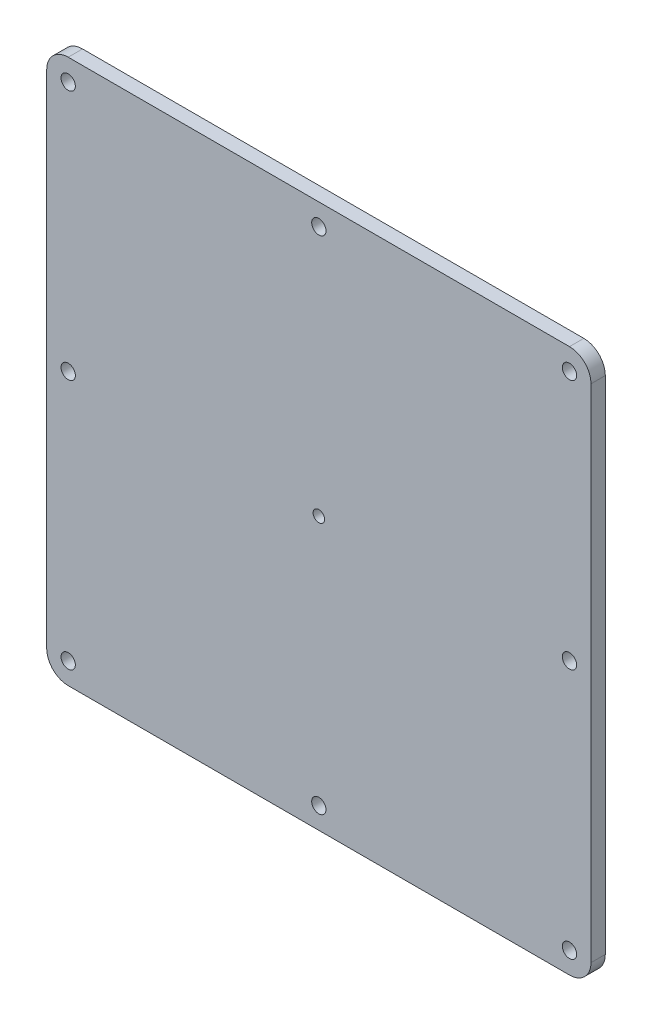
SolidWorks part; units mm, degrees
ref_plane "Front Plane" through (0, 0, 0) normal (0, 0, 1) x (1, 0, 0)
ref_plane "Top Plane" through (0, 0, 0) normal (0, 1, 0) x (1, 0, 0)
ref_plane "Right Plane" through (0, 0, 0) normal (1, 0, 0) x (0, 0, -1)
sketch "Sketch2" plane through (0, 0, 0) normal (0, 0, 1) x (1, 0, 0)
  line L0 (-175, 175) -> (175, 175) construction
  line L1 (-175, 190) -> (175, 190)
  line L2 (-190, 175) -> (-190, -175)
  line L3 (-175, -190) -> (175, -190)
  line L4 (190, 175) -> (190, -175)
  line L5 (-190, 190) -> (190, -190) construction
  line L6 (-190, -190) -> (190, 190) construction
  line L7 (175, 175) -> (175, -175) construction
  line L8 (175, -175) -> (-175, -175) construction
  line L9 (-175, -175) -> (-175, 175) construction
  arc A0 (-190, -175) -> (-175, -190) centre (-175, -175) ccw
  arc A1 (175, -190) -> (190, -175) centre (175, -175) ccw
  arc A2 (175, 190) -> (190, 175) centre (175, 175) cw
  arc A3 (-175, 190) -> (-190, 175) centre (-175, 175) ccw
  circle A4 centre (-175, 175) radius 5
  circle A5 centre (0, 175) radius 5
  circle A6 centre (175, 175) radius 5
  circle A14 centre (175, 0) radius 5
  circle A15 centre (-175, 0) radius 5
  circle A16 centre (-175, -175) radius 5
  circle A17 centre (0, -175) radius 5
  circle A18 centre (175, -175) radius 5
  circle A19 centre (0, 0) radius 4
  point P0 (0, 0)
  dimension "D3" = 15
  dimension "D4" = 10
  dimension "D5" = 10
  dimension "D6" = 10
  dimension "D7" = 8
  dimension "D8" = 10
  dimension "D9" = 10
  dimension "D10" = 10
  dimension "D11" = 10
  dimension "D1" = 380
  dimension "D2" = 380
extrude "Boss-Extrude1" add sketch "Sketch2" along normal blind 10
